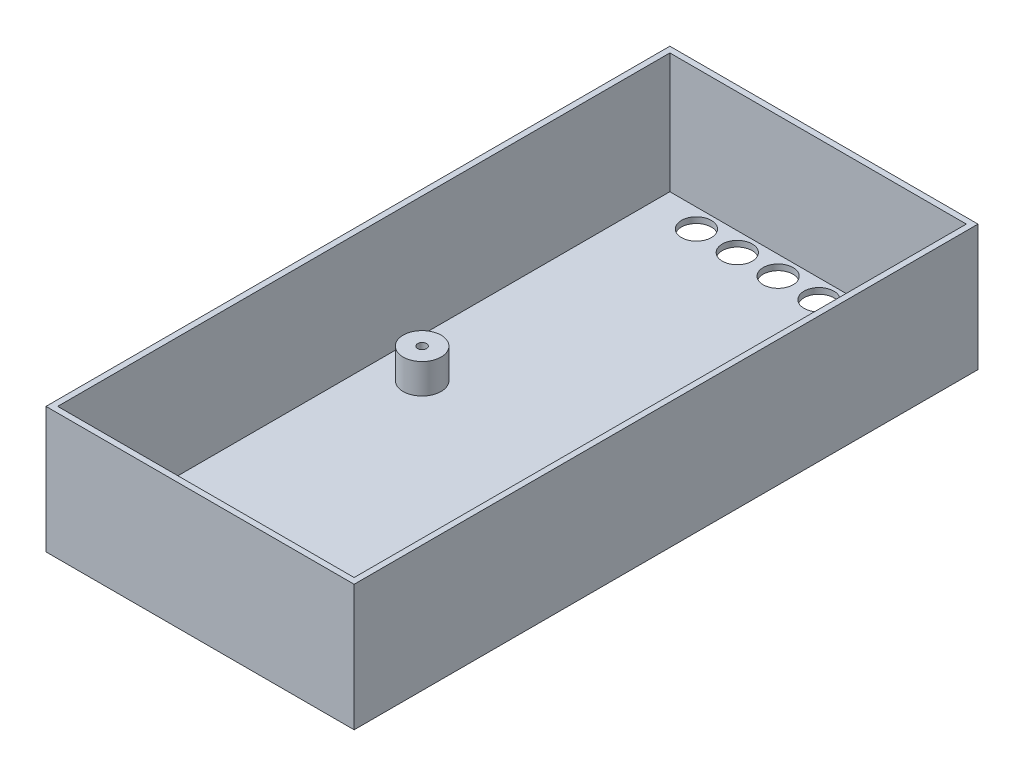
SolidWorks part; units mm, degrees
ref_plane "Front Plane" through (0, 0, 0) normal (0, 0, 1) x (1, 0, 0)
ref_plane "Top Plane" through (0, 0, 0) normal (0, 1, 0) x (1, 0, 0)
ref_plane "Right Plane" through (0, 0, 0) normal (1, 0, 0) x (0, 0, -1)
sketch "Sketch1" plane through (0, 0, 0) normal (0, 1, 0) x (1, 0, 0)
  line L0 (25.4, 71.12) -> (76.2, 71.12) construction
  line L1 (76.2, 71.12) -> (76.2, 7.62) construction
  line L2 (76.2, 7.62) -> (25.4, 7.62) construction
  line L3 (25.4, 7.62) -> (25.4, 71.12) construction
  line L4 (20.574, -1.27) -> (82.55, -1.27) construction
  line L5 (82.55, -1.27) -> (82.55, -58.928) construction
  line L6 (82.55, -58.928) -> (20.574, -58.928) construction
  line L7 (20.574, -58.928) -> (20.574, -1.27) construction
  line L8 (0, 0) -> (0, 117.5016) construction
  line L9 (0, 0) -> (291.9946, 0) construction
  line L10 (21.844, 75.226) -> (21.844, -87.633) construction
  line L11 (81.28, 79.308) -> (81.28, -92.8499) construction
  line L12 (8.7267, 72.7075) -> (138.7499, 72.7075) construction
  line L13 (19.304, 76.5736) -> (19.304, -95.9725) construction
  line L14 (83.82, 80.4155) -> (83.82, -149.0254) construction
  line L15 (10.8384, -60.5155) -> (110.221, -60.5155) construction
  line L16 (15.8238, 68.58) -> (121.75, 68.58) construction
  line L17 (64.516, 58.674) -> (77.724, 58.674)
  line L18 (64.516, 58.674) -> (64.516, 45.466)
  line L19 (64.516, 45.466) -> (77.724, 45.466)
  line L20 (77.724, 58.674) -> (77.724, 45.466)
  line L22 (19.304, 72.7075) -> (83.82, 72.7075)
  line L23 (19.304, 72.7075) -> (19.304, -60.5155)
  line L24 (19.304, -60.5155) -> (83.82, -60.5155)
  line L25 (83.82, 72.7075) -> (83.82, -60.5155)
  circle A0 centre (29.21, 68.58) radius 3.25
  circle A1 centre (38.1, 68.58) radius 3.25
  circle A2 centre (46.99, 68.58) radius 3.25
  circle A3 centre (55.88, 68.58) radius 3.25
  circle A4 centre (73.66, 68.58) radius 0.9652
  circle A5 centre (73.66, 10.16) radius 0.9652
  circle A6 centre (27.94, 10.16) radius 0.9652
  point P28 (71.12, 58.674)
  dimension "D24" = 6.5
  dimension "D25" = 6.5
  dimension "D26" = 6.5
  dimension "D27" = 6.5
  dimension "D34" = 1.9304
  dimension "D35" = 1.9304
  dimension "D36" = 1.9304
  dimension "D1" = 25.4
  dimension "D2" = 76.2
  dimension "D3" = 7.62
  dimension "D4" = 71.12
  dimension "D5" = 8.89
  dimension "D6" = 61.976
  dimension "D7" = 57.658
  dimension "D8" = 21.844
  dimension "D9" = 81.28
  dimension "D10" = 1.5875
  dimension "D11" = 2.54
  dimension "D12" = 2.54
  dimension "D13" = 1.27
  dimension "D14" = 1.5875
  dimension "D15" = 64.516
  dimension "D16" = 77.724
  dimension "D17" = 45.466
  dimension "D18" = 58.674
  dimension "D19" = 68.58
  dimension "D20" = 55.88
  dimension "D21" = 46.99
  dimension "D22" = 38.1
  dimension "D23" = 29.21
  dimension "D28" = 27.94
  dimension "D29" = 10.16
  dimension "D30" = 73.66
  dimension "D31" = 10.16
  dimension "D32" = 73.66
  dimension "D33" = 68.58
extrude "front_face" add sketch "Sketch1" along normal blind 1.27
sketch "Sketch2" plane through (0, 1.27, 0) normal (0, 1, 0) x (1, 0, 0)
  circle A0 centre (27.94, 10.16) radius 4.1275
  circle A1 centre (73.66, 10.16) radius 4.1275
  circle A2 centre (73.66, 68.58) radius 4.064
  circle A3 centre (27.94, 10.16) radius 0.9652
  circle A4 centre (73.66, 10.16) radius 0.9652
  circle A5 centre (73.66, 68.58) radius 0.9652
  point P0 (73.66, 68.58)
  point P1 (73.66, 10.16)
  point P3 (27.94, 10.16)
  dimension "D1" = 8.128
  dimension "D2" = 8.255
  dimension "D3" = 8.255
extrude "screw_post_PCB" add sketch "Sketch2" along normal blind 6.5
sketch "Sketch5" plane through (0, 0, -72.7075) normal (0, 0, -1) x (-1, 0, 0)
  line L1 (-83.82, 0) -> (-85.09, 0)
  line L2 (-83.82, 0) -> (-83.82, 27.432)
  line L3 (-83.82, 27.432) -> (-85.09, 27.432)
  line L4 (-85.09, 0) -> (-85.09, 27.432)
  line L5 (-19.304, 0) -> (-18.034, 0)
  line L6 (-19.304, 0) -> (-19.304, 27.432)
  line L7 (-19.304, 27.432) -> (-18.034, 27.432)
  line L8 (-18.034, 0) -> (-18.034, 27.432)
  dimension "D1" = 1.27
  dimension "D2" = 27.432
  dimension "D3" = 27.432
  dimension "D4" = 1.27
extrude "side_walls" add sketch "Sketch5" against normal up to surface (133.223 mm away) up to face at (51.562, 0.635, 60.5155)
sketch "Sketch6" plane through (85.09, 0, 0) normal (1, 0, 0) x (0, 0, -1)
  line L1 (-60.5155, 0) -> (-61.7855, 0)
  line L2 (-60.5155, 0) -> (-60.5155, 27.432)
  line L3 (-60.5155, 27.432) -> (-61.7855, 27.432)
  line L4 (-61.7855, 0) -> (-61.7855, 27.432)
  dimension "D3" = 1.27
  dimension "D4" = 27.432
extrude "bottom_wall" add sketch "Sketch6" against normal up to surface (67.056 mm away) up to face at (18.034, 13.716, -6.096)
sketch "Sketch8" plane through (0, 0, -72.7075) normal (0, 0, -1) x (-1, 0, 0)
  line L0 (-85.09, 27.432) -> (-85.09, 0)
  line L1 (-85.09, 0) -> (-18.034, 0)
  line L2 (-18.034, 0) -> (-18.034, 27.432)
  line L8 (-85.09, 27.432) -> (-18.034, 27.432)
extrude "top_wall" add sketch "Sketch8" along normal blind 1.27
